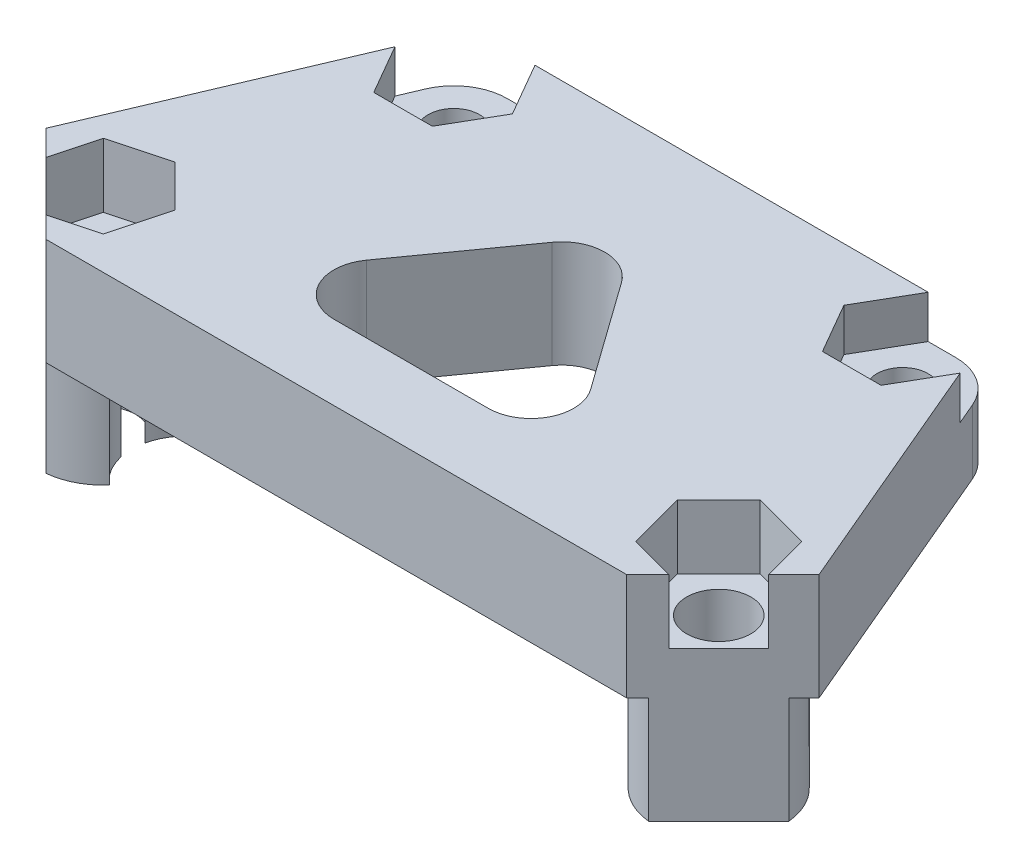
SolidWorks part; units mm, degrees
ref_plane "Front" through (0, 0, 0) normal (0, 0, 1) x (1, 0, 0)
ref_plane "Top" through (0, 0, 0) normal (0, 1, 0) x (1, 0, 0)
ref_plane "Right" through (0, 0, 0) normal (1, 0, 0) x (0, 0, -1)
sketch "Sketch1" plane through (0, 0, 0) normal (0, 1, 0) x (1, 0, 0)
  line L0 (-10.5, 0) -> (10.5, 0) construction
  line L5 (0, 0) -> (0, -2) construction
  line L6 (-10.5, 2.5) -> (10.5, 2.5)
  line L7 (-20, -16) -> (20, -16)
  line L8 (20, -16) -> (12.8016, 0.976)
  line L9 (-20, -16) -> (-12.8016, 0.976)
  line L10 (0, -2) -> (-7.5, -12.5)
  line L11 (-7.5, -12.5) -> (7.5, -12.5)
  line L12 (7.5, -12.5) -> (0, -2)
  line L13 (13.0213, -16) -> (17.922, -11.0994) construction
  line L14 (18.0904, -11.4966) -> (13.587, -16)
  line L15 (0, -50) -> (0, 50) construction
  line L16 (-18.0904, -11.4966) -> (-13.587, -16)
  circle A0 centre (-10.5, 0) radius 2.5
  circle A1 centre (10.5, 0) radius 2.5
  circle A2 centre (-14.4, -12.5) radius 1.5
  circle A3 centre (14.4, -12.5) radius 1.5
  dimension "D3" = 5
  dimension "D5" = 3
  dimension "D2" = 2
  dimension "D4" = 21
  dimension "D6" = 12.5
  dimension "D7" = 28.8
  dimension "D8" = 3.5
  dimension "D9" = 40
  dimension "D10" = 15
  dimension "D11" = 45
  dimension "D12" = 0.4
extrude "Boss-Extrude1" add sketch "Sketch1" along normal blind 5 contours A1 L6 A0 L9 L16 L7 L14 L8 A3 A2 L12 L11 L10 | A0 | A1
hole_wizard "M2 Clearance Hole1" positions "Sketch2" profile "Sketch3" hole size "M2" standard "ANSI Metric" end condition through all
sketch "Sketch2" plane through (0, 5, 0) normal (0, 1, 0) x (1, 0, 0)
  point P5 (-10.5, 0)
  point P8 (10.5, 0)
sketch "Sketch3" plane through (-10.5, 5, 0) normal (1, 0, 0) x (0, 0, 1)
  line L0 (0, 0) -> (0, 5)
  line L1 (0, 5) -> (1.2, 5)
  line L2 (1.2, 5) -> (1.2, 0)
  line L5 (1.2, 0) -> (0, 0)
  line L11 (0, -6.35) -> (0, 107.95) construction
  dimension "Thru Hole Dia." = 2.4
  dimension "Thru Hole Depth" = 5
fillet "Fillet1" radius 2 3 edges at (7.5, 2.5, 12.5) (-7.5, 2.5, 12.5) (0, 2.5, 2)
sketch "Sketch4" plane through (0, 0, 0) normal (0, -1, 0) x (1, 0, 0)
  line L0 (11.8103, 10.2833) -> (-9.2279, -2.1521) construction
  line L1 (-11.7853, 2.1443) -> (9.1761, 14.7086) construction
  line L2 (0, -50) -> (0, 50) construction
  arc A0 (-12.8016, -0.976) -> (-10.5, -2.5) centre (-10.5, 0) ccw construction
  arc A1 (10.5, -2.5) -> (12.8016, -0.976) centre (10.5, 0) ccw construction
  arc A2 (-12.8016, -0.976) -> (-10.5, -2.5) centre (-10.5, 0) ccw
  arc A3 (10.5, -2.5) -> (12.8016, -0.976) centre (10.5, 0) ccw
  arc A4 (11.8103, 10.2833) -> (9.1761, 14.7086) centre (10.5, 12.5) ccw
  circle A5 centre (14.4, 12.5) radius 1.5 construction
  circle A6 centre (14.4, 12.5) radius 1.5
  circle A7 centre (-10.5, 0) radius 2.5 construction
  circle A8 centre (14.4, 12.5) radius 3
  arc A9 (9.1761, 14.7086) -> (11.8103, 10.2833) centre (10.5, 12.5) ccw construction
  circle A10 centre (-14.4, 12.5) radius 3
  arc A11 (-11.8103, 10.2833) -> (-9.1761, 14.7086) centre (-10.5, 12.5) cw
  circle M9 centre (14.4, 12.5) radius 1.5
  circle M10 centre (-14.4, 12.5) radius 1.5
  dimension "D1" = 5.15
  dimension "D2" = 6
extrude "Boss-Extrude2" add sketch "Sketch4" along normal blind 5 contours A4 A8 M9 | A10 A11 M10
sketch "Sketch5" plane through (0, 5, 0) normal (0, 1, 0) x (1, 0, 0)
  line L1 (15.1098, -15.149) -> (17.049, -13.2098)
  line L2 (17.049, -13.2098) -> (16.3392, -10.5608)
  line L3 (16.3392, -10.5608) -> (13.6902, -9.851)
  line L4 (13.6902, -9.851) -> (11.751, -11.7902)
  line L5 (11.751, -11.7902) -> (12.4608, -14.4392)
  line L6 (12.4608, -14.4392) -> (15.1098, -15.149)
  line L8 (0, -50) -> (0, 50) construction
  line L9 (-12.4608, -14.4392) -> (-15.1098, -15.149)
  line L10 (-11.751, -11.7902) -> (-12.4608, -14.4392)
  line L11 (-13.6902, -9.851) -> (-11.751, -11.7902)
  line L12 (-16.3392, -10.5608) -> (-13.6902, -9.851)
  line L13 (-17.049, -13.2098) -> (-16.3392, -10.5608)
  line L14 (-15.1098, -15.149) -> (-17.049, -13.2098)
  line L15 (-13.587, -16) -> (13.587, -16) construction
  circle A0 centre (14.4, -12.5) radius 1.5 construction
  circle A1 centre (14.4, -12.5) radius 1.5
  circle A2 centre (14.4, -12.5) radius 2.375 construction
  dimension "D1" = 4.75
  dimension "D2" = 45
extrude "Cut-Extrude1" cut sketch "Sketch5" against normal blind 3
sketch "Sketch6" plane through (0, 5, 0) normal (0, 1, 0) x (1, 0, 0)
  line L0 (-10.5, 2.5) -> (10.5, 2.5) construction
  line L1 (9.1288, -2.375) -> (11.8712, -2.375)
  line L2 (11.8712, -2.375) -> (13.2424, 0)
  line L3 (13.2424, 0) -> (11.8712, 2.375)
  line L4 (11.8712, 2.375) -> (9.1288, 2.375)
  line L5 (9.201, 2.5) -> (7.7576, 0)
  line L6 (7.7576, 0) -> (9.1288, -2.375)
  line L7 (0, -50) -> (0, 50) construction
  line L8 (18.0904, -11.4966) -> (12.8016, 0.976) construction
  line L9 (-7.7576, 0) -> (-9.1288, -2.375)
  line L10 (-9.201, 2.5) -> (-7.7576, 0)
  line L11 (-11.8712, 2.375) -> (-9.1288, 2.375)
  line L12 (-13.2424, 0) -> (-11.8712, 2.375)
  line L13 (-11.8712, -2.375) -> (-13.2424, 0)
  line L14 (-9.1288, -2.375) -> (-11.8712, -2.375)
  line L15 (-18.0904, -11.4966) -> (-12.8016, 0.976) construction
  line L16 (18.0904, -11.4966) -> (12.8016, 0.976)
  line L17 (-10.5, 2.5) -> (10.5, 2.5)
  line L18 (-18.0904, -11.4966) -> (-12.8016, 0.976)
  circle A0 centre (10.5, 0) radius 1.2 construction
  circle A1 centre (10.5, 0) radius 1.2
  circle A2 centre (10.5, 0) radius 2.375 construction
  arc A3 (12.8016, 0.976) -> (10.5, 2.5) centre (10.5, 0) ccw construction
  arc A4 (-10.5, 2.5) -> (-12.8016, 0.976) centre (-10.5, 0) ccw construction
  arc A5 (12.8016, 0.976) -> (10.5, 2.5) centre (10.5, 0) ccw
  arc A6 (-10.5, 2.5) -> (-12.8016, 0.976) centre (-10.5, 0) ccw
  point P26 (-8.6932, 2.5)
  point P29 (0, 0)
  circle M19 centre (-10.5, 0) radius 1.2
  circle M20 centre (10.5, 0) radius 1.2
  line M21 (18.0904, -11.4966) -> (12.8016, 0.976)
  arc M22 (12.8016, 0.976) -> (10.5, 2.5) centre (10.5, 0) ccw
  line M23 (10.5, 2.5) -> (-10.5, 2.5)
  arc M24 (-10.5, 2.5) -> (-12.8016, 0.976) centre (-10.5, 0) ccw
  line M25 (-12.8016, 0.976) -> (-18.0904, -11.4966)
  dimension "D1" = 4.75
extrude "Cut-Extrude2" cut sketch "Sketch6" against normal blind 2 contours L14 L9 L10 L11 L12 L13 M24 M25 M19 | L12 M25 M24 | L11 L10 M24 M23 | L5 L6 L1 L2 L3 L4 M21 M22 M20 | L3 M21 M22 | L5 L4 M23 M22
